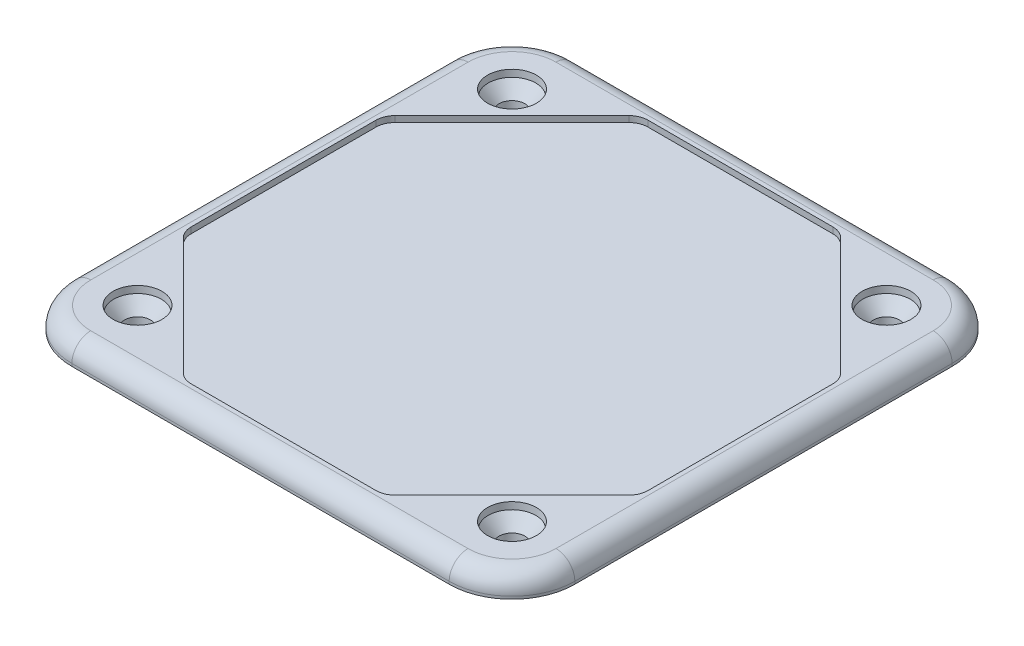
SolidWorks part; units mm, degrees
ref_plane "Front Plane" through (0, 0, 0) normal (0, 0, 1) x (1, 0, 0)
ref_plane "Top Plane" through (0, 0, 0) normal (0, 1, 0) x (1, 0, 0)
ref_plane "Right Plane" through (0, 0, 0) normal (1, 0, 0) x (0, 0, -1)
sketch "Sketch1" plane through (0, 0, 0) normal (0, 1, 0) x (1, 0, 0)
  line L0 (31.8135, 31.8135) -> (-31.8135, 31.8135)
  line L1 (-31.8135, 31.8135) -> (-31.8135, -31.8135)
  line L2 (-31.8135, -31.8135) -> (31.8135, -31.8135)
  line L3 (31.8135, -31.8135) -> (31.8135, 31.8135)
extrude "Boss-Extrude1" add sketch "Sketch1" against normal blind 2.7178
sketch "Sketch2" plane through (0, 0, 0) normal (0, 1, 0) x (-1, 0, 0)
  line L0 (12.6857, -28.8925) -> (28.8925, -12.6857)
  line L1 (28.8925, -12.6857) -> (28.8925, 12.6857)
  line L2 (28.8925, 12.6857) -> (12.6857, 28.8925)
  line L3 (12.6857, 28.8925) -> (-12.6857, 28.8925)
  line L4 (-12.6857, 28.8925) -> (-28.8925, 12.6857)
  line L5 (-28.8925, 12.6857) -> (-28.8925, -12.6857)
  line L6 (-28.8925, -12.6857) -> (-12.6857, -28.8925)
  line L7 (-12.6857, -28.8925) -> (12.6857, -28.8925)
  dimension "D1" = 25.3714
  dimension "D2" = 25.3714
  dimension "D3" = 25.3714
  dimension "D4" = 25.3714
  dimension "D5" = 22.9199
  dimension "D6" = 22.9199
extrude "Cut-Extrude1" cut sketch "Sketch2" against normal blind 0.762
sketch "Sketch3" plane through (0, -2.7178, 0) normal (0, -1, 0) x (1, 0, 0)
  line L0 (29.1465, -29.1465) -> (-29.1465, -29.1465)
  line L1 (-29.1465, -29.1465) -> (-29.1465, 29.1465)
  line L2 (-29.1465, 29.1465) -> (29.1465, 29.1465)
  line L3 (29.1465, 29.1465) -> (29.1465, -29.1465)
extrude "Boss-Extrude2" add sketch "Sketch3" along normal blind 1.6002
sketch "Sketch4" plane through (0, -4.318, 0) normal (0, -1, 0) x (1, 0, 0)
  line L0 (-27.5463, -27.5463) -> (27.5463, -27.5463)
  line L1 (27.5463, -27.5463) -> (27.5463, 27.5463)
  line L2 (27.5463, 27.5463) -> (-27.5463, 27.5463)
  line L3 (-27.5463, 27.5463) -> (-27.5463, -27.5463)
extrude "Cut-Extrude2" cut sketch "Sketch4" against normal blind 1.6002
ref_plane "Plane1" through (0, 0, -23.6855) normal (0, 0, -1) x (-1, 0, 0)
sketch "Sketch5" plane through (0, 0, -23.6855) normal (0, 0, -1) x (-1, 0, 0)
  line L0 (20.5105, -4.318) -> (23.6855, -4.318)
  line L1 (23.6855, -4.318) -> (23.6855, -2.7178)
  line L2 (23.6855, -2.7178) -> (20.5105, -2.7178)
  line L3 (20.5105, -2.7178) -> (20.5105, -4.318)
  line L4 (23.6855, -4.318) -> (23.6855, -2.7178) construction
revolve "Revolve1" add sketch "Sketch5" angle 360 about L4
ref_plane "Plane2" through (0, 0, 23.6855) normal (0, 0, -1) x (-1, 0, 0)
sketch "Sketch6" plane through (0, 0, 23.6855) normal (0, 0, -1) x (-1, 0, 0)
  line L0 (-26.8605, -4.318) -> (-23.6855, -4.318)
  line L1 (-23.6855, -4.318) -> (-23.6855, -2.7178)
  line L2 (-23.6855, -2.7178) -> (-26.8605, -2.7178)
  line L3 (-26.8605, -2.7178) -> (-26.8605, -4.318)
  line L4 (-23.6855, -4.318) -> (-23.6855, -2.7178) construction
revolve "Revolve2" add sketch "Sketch6" angle 360 about L4
sketch "Sketch7" plane through (0, 0, 23.6855) normal (0, 0, -1) x (-1, 0, 0)
  line L0 (20.5105, -4.318) -> (23.6855, -4.318)
  line L1 (23.6855, -4.318) -> (23.6855, -2.7178)
  line L2 (23.6855, -2.7178) -> (20.5105, -2.7178)
  line L3 (20.5105, -2.7178) -> (20.5105, -4.318)
  line L4 (23.6855, -4.318) -> (23.6855, -2.7178) construction
revolve "Revolve3" add sketch "Sketch7" angle 360 about L4
sketch "Sketch8" plane through (0, 0, -23.6855) normal (0, 0, -1) x (-1, 0, 0)
  line L0 (-26.8605, -4.318) -> (-23.6855, -4.318)
  line L1 (-23.6855, -4.318) -> (-23.6855, -2.7178)
  line L2 (-23.6855, -2.7178) -> (-26.8605, -2.7178)
  line L3 (-26.8605, -2.7178) -> (-26.8605, -4.318)
  line L4 (-23.6855, -4.318) -> (-23.6855, -2.7178) construction
revolve "Revolve4" add sketch "Sketch8" angle 360 about L4
ref_plane "Plane3" through (0, 0, -23.6855) normal (0, 0, 1) x (1, 0, 0)
sketch "Sketch9" plane through (0, 0, -23.6855) normal (0, 0, 1) x (1, 0, 0)
  line L0 (-20.5994, 0) -> (-23.6855, 0)
  line L1 (-23.6855, 0) -> (-23.6855, -4.318)
  line L2 (-23.6855, -4.318) -> (-22.2123, -4.318)
  line L3 (-22.2123, -4.318) -> (-22.0458, -2.4149)
  line L4 (-22.0458, -2.4149) -> (-20.6725, -0.835)
  line L5 (-20.6725, -0.835) -> (-20.5994, 0)
  line L6 (-23.6855, 0) -> (-23.6855, -4.318) construction
revolve "Cut-Revolve1" cut sketch "Sketch9" angle 360 about L6
ref_plane "Plane4" through (0, 0, 23.6855) normal (0, 0, 1) x (1, 0, 0)
sketch "Sketch10" plane through (0, 0, 23.6855) normal (0, 0, 1) x (1, 0, 0)
  line L0 (26.7716, 0) -> (23.6855, 0)
  line L1 (23.6855, 0) -> (23.6855, -4.318)
  line L2 (23.6855, -4.318) -> (25.1587, -4.318)
  line L3 (25.1587, -4.318) -> (25.3252, -2.4149)
  line L4 (25.3252, -2.4149) -> (26.6985, -0.835)
  line L5 (26.6985, -0.835) -> (26.7716, 0)
  line L6 (23.6855, 0) -> (23.6855, -4.318) construction
revolve "Cut-Revolve2" cut sketch "Sketch10" angle 360 about L6
sketch "Sketch11" plane through (0, 0, 23.6855) normal (0, 0, 1) x (1, 0, 0)
  line L0 (-20.5994, 0) -> (-23.6855, 0)
  line L1 (-23.6855, 0) -> (-23.6855, -4.318)
  line L2 (-23.6855, -4.318) -> (-22.2123, -4.318)
  line L3 (-22.2123, -4.318) -> (-22.0458, -2.4149)
  line L4 (-22.0458, -2.4149) -> (-20.6725, -0.835)
  line L5 (-20.6725, -0.835) -> (-20.5994, 0)
  line L6 (-23.6855, 0) -> (-23.6855, -4.318) construction
revolve "Cut-Revolve3" cut sketch "Sketch11" angle 360 about L6
sketch "Sketch12" plane through (0, 0, -23.6855) normal (0, 0, 1) x (1, 0, 0)
  line L0 (26.7716, 0) -> (23.6855, 0)
  line L1 (23.6855, 0) -> (23.6855, -4.318)
  line L2 (23.6855, -4.318) -> (25.1587, -4.318)
  line L3 (25.1587, -4.318) -> (25.3252, -2.4149)
  line L4 (25.3252, -2.4149) -> (26.6985, -0.835)
  line L5 (26.6985, -0.835) -> (26.7716, 0)
  line L6 (23.6855, 0) -> (23.6855, -4.318) construction
revolve "Cut-Revolve4" cut sketch "Sketch12" angle 360 about L6
fillet "Fillet1" radius 7.9502 4 edges at (31.8135, -1.3589, 31.8135) (-31.8135, -1.3589, -31.8135) (-31.8135, -1.3589, 31.8135) (31.8135, -1.3589, -31.8135)
fillet "Fillet2" radius 2.3876 16 edges at (-12.6857, -0.381, -28.8925) (29.4849, 0, 29.4849) (31.8135, 0, 0) (0, 0, 31.8135) (29.4849, 0, -29.4849) (-29.4849, 0, 29.4849) (0, 0, -31.8135) (-31.8135, 0, 0) (-29.4849, 0, -29.4849) (12.6857, -0.381, 28.8925) (-12.6857, -0.381, 28.8925) (-28.8925, -0.381, -12.6857) (28.8925, -0.381, 12.6857) (28.8925, -0.381, -12.6857) (12.6857, -0.381, -28.8925) (-28.8925, -0.381, 12.6857)
fillet "Fillet3" radius 3.683 4 edges at (-27.5463, -3.5179, 27.5463) (27.5463, -3.5179, 27.5463) (-27.5463, -3.5179, -27.5463) (27.5463, -3.5179, -27.5463)
fillet "Fillet4" radius 5.2832 4 edges at (29.1465, -3.5179, 29.1465) (29.1465, -3.5179, -29.1465) (-29.1465, -3.5179, -29.1465) (-29.1465, -3.5179, 29.1465)
